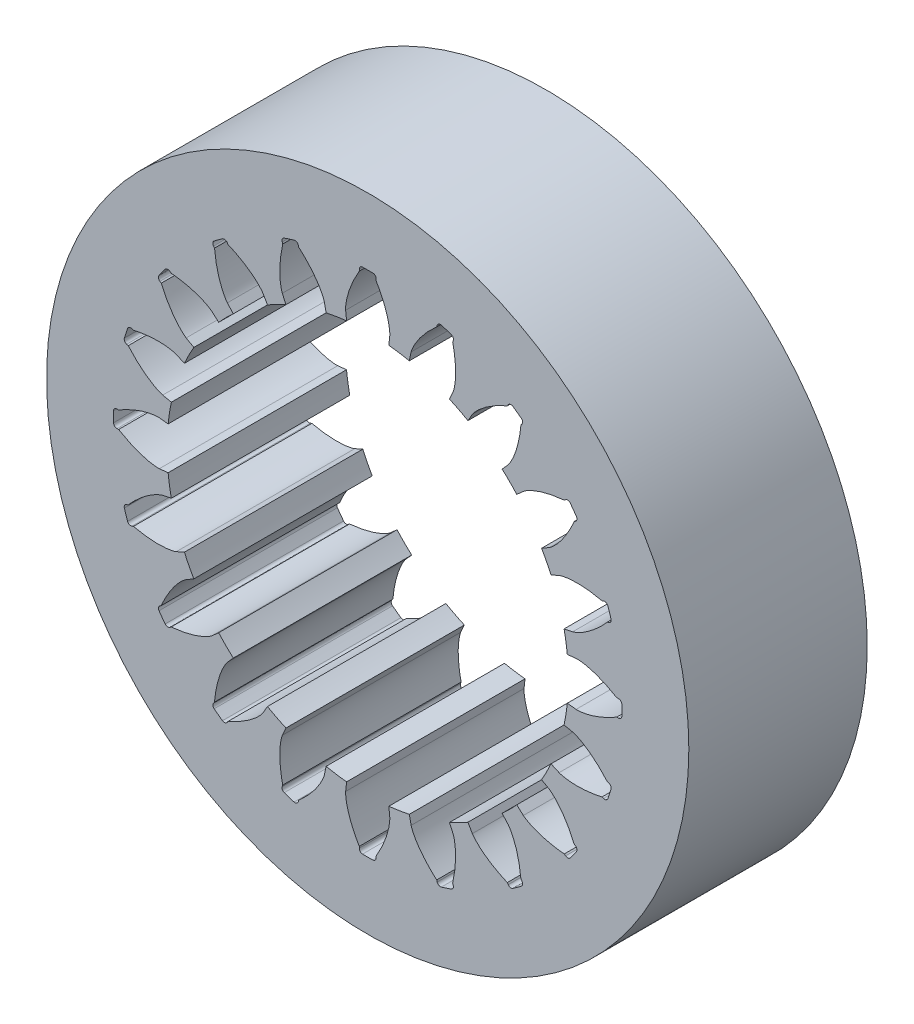
SolidWorks part; units mm, degrees
ref_plane "Front Plane" through (0, 0, 0) normal (0, 0, 1) x (1, 0, 0)
ref_plane "Top Plane" through (0, 0, 0) normal (0, 1, 0) x (1, 0, 0)
ref_plane "Right Plane" through (0, 0, 0) normal (1, 0, 0) x (0, 0, -1)
ref_axis "Gear Axis" through (0, 0, -0.5001) along (0, 0, 1)
sketch "Blank Sketch" plane through (0, 0, 0) normal (0, 0, 1) x (1, 0, 0)
  circle A0 centre (0, 0) radius 18
  circle A1 centre (0, 0) radius 11.25
  dimension "Rim" = 36
  dimension "Tip" = 22.5
extrude "Blank" add sketch "Blank Sketch" along normal blind 10
sketch "Tooth Space Sketch" plane through (0, 0, 0) normal (0, 0, 1) x (1, 0, 0)
  line L0 (11.6809, 1.2363) -> (9.9445, 1.0525)
  line L1 (11.6809, -1.2363) -> (9.9445, -1.0525)
  line L2 (9.9445, 1.0525) -> (9.9445, -1.0525)
  line L3 (13.9608, 0.4707) -> (14.0533, 0.4738)
  line L4 (13.9608, -0.4707) -> (14.0533, -0.4738)
  circle A0 centre (0, 0) radius 10 construction
  arc A1 (14.247, 0.2902) -> (14.0533, 0.4738) centre (14.0596, 0.2864) ccw
  arc A2 (14.0533, -0.4738) -> (14.247, -0.2902) centre (14.0596, -0.2864) ccw
  arc A3 (14.247, -0.2902) -> (14.247, 0.2902) centre (0, 0) ccw
  spline S0 degree 4 poles (11.6809, 1.2363) (11.6845, 1.2366) (11.6946, 1.2374) (11.7136, 1.2382) (11.7448, 1.2388) (11.7846, 1.2383) (11.8361, 1.2362) (11.8968, 1.2318) (11.9635, 1.2251) (12.0361, 1.2157) (12.1085, 1.2045) (12.1806, 1.1917) (12.2524, 1.1773) (12.3392, 1.1581) (12.4432, 1.1325) (12.5644, 1.0989) (12.7014, 1.0564) (12.8404, 1.0086) (12.9768, 0.9577) (13.114, 0.902) (13.2462, 0.845) (13.3827, 0.7815) (13.5084, 0.7205) (13.6482, 0.6474) (13.7608, 0.5871) (13.9081, 0.5023) (13.9948, 0.4507) (14.0959, 0.3886) (14.1405, 0.36) (14.168, 0.3425) knots 0 0 0 0 0 0.005377 0.015084 0.028532 0.04661 0.064855 0.092111 0.119476 0.146842 0.174209 0.201575 0.228941 0.256307 0.307035 0.361767 0.4165 0.471232 0.525964 0.580697 0.635429 0.690161 0.744894 0.799626 0.854358 0.909091 0.954545 1 1 1 1 1 construction
  spline S1 degree 4 poles (11.6809, 1.2363) (11.6845, 1.2366) (11.6946, 1.2374) (11.7136, 1.2382) (11.7448, 1.2388) (11.7846, 1.2383) (11.8361, 1.2362) (11.8968, 1.2318) (11.9635, 1.2251) (12.0361, 1.2157) (12.1085, 1.2045) (12.1806, 1.1917) (12.2524, 1.1773) (12.3392, 1.1581) (12.4432, 1.1325) (12.5644, 1.0989) (12.7014, 1.0564) (12.8404, 1.0086) (12.9768, 0.9577) (13.114, 0.902) (13.2462, 0.845) (13.3827, 0.7815) (13.5084, 0.7205) (13.6482, 0.6474) (13.7608, 0.5871) (13.8762, 0.5207) (13.9322, 0.4878) (13.9608, 0.4707) knots 0 0 0 0 0 0.005377 0.015084 0.028532 0.04661 0.064855 0.092111 0.119476 0.146842 0.174209 0.201575 0.228941 0.256307 0.307035 0.361767 0.4165 0.471232 0.525964 0.580697 0.635429 0.690161 0.744894 0.799626 0.854358 0.909091 0.909091 0.909091 0.909091 0.909091
  spline S2 degree 4 poles (11.6809, -1.2363) (11.6845, -1.2366) (11.6946, -1.2374) (11.7136, -1.2382) (11.7448, -1.2388) (11.7846, -1.2383) (11.8361, -1.2362) (11.8968, -1.2318) (11.9635, -1.2251) (12.0361, -1.2157) (12.1085, -1.2045) (12.1806, -1.1917) (12.2524, -1.1773) (12.3392, -1.1581) (12.4432, -1.1325) (12.5644, -1.0989) (12.7014, -1.0564) (12.8404, -1.0086) (12.9768, -0.9577) (13.114, -0.902) (13.2462, -0.845) (13.3827, -0.7815) (13.5084, -0.7205) (13.6482, -0.6474) (13.7608, -0.5871) (13.9081, -0.5023) (13.9948, -0.4507) (14.0959, -0.3886) (14.1405, -0.36) (14.168, -0.3425) knots 0 0 0 0 0 0.005377 0.015084 0.028532 0.04661 0.064855 0.092111 0.119476 0.146842 0.174209 0.201575 0.228941 0.256307 0.307035 0.361767 0.4165 0.471232 0.525964 0.580697 0.635429 0.690161 0.744894 0.799626 0.854358 0.909091 0.954545 1 1 1 1 1 construction
  spline S3 degree 4 poles (11.6809, -1.2363) (11.6845, -1.2366) (11.6946, -1.2374) (11.7136, -1.2382) (11.7448, -1.2388) (11.7846, -1.2383) (11.8361, -1.2362) (11.8968, -1.2318) (11.9635, -1.2251) (12.0361, -1.2157) (12.1085, -1.2045) (12.1806, -1.1917) (12.2524, -1.1773) (12.3392, -1.1581) (12.4432, -1.1325) (12.5644, -1.0989) (12.7014, -1.0564) (12.8404, -1.0086) (12.9768, -0.9577) (13.114, -0.902) (13.2462, -0.845) (13.3827, -0.7815) (13.5084, -0.7205) (13.6482, -0.6474) (13.7608, -0.5871) (13.8762, -0.5207) (13.9322, -0.4878) (13.9608, -0.4707) knots 0 0 0 0 0 0.005377 0.015084 0.028532 0.04661 0.064855 0.092111 0.119476 0.146842 0.174209 0.201575 0.228941 0.256307 0.307035 0.361767 0.4165 0.471232 0.525964 0.580697 0.635429 0.690161 0.744894 0.799626 0.854358 0.909091 0.909091 0.909091 0.909091 0.909091
  dimension "Root" = 14.25
  dimension "Fillet" = 0.1875
  dimension "Cap" = 20
extrude "Tooth Space" cut sketch "Tooth Space Sketch" against normal through all both and the other way through all both
pattern_circular "Teeth" count 20 over 360 about axis through (0, 0, -0.5001) along (0, 0, 1) of "Tooth Space"
equation "\"No. of Teeth\"= 20"
equation "\"Module\"= 1.25"
equation "\"Pressure Angle\"= 20"
equation "\"Inner Diameter\"= ( \"No. of Teeth\" - 2 ) * \"Module\""
equation "\"Pitch Diameter\"= \"No. of Teeth\" * \"Module\""
equation "\"Backlash\"= IIF ( \"Module\" <= 1 , 0.3 * \"Module\" , 0.3 )"
equation "\"Arc Length\"= ( ( \"Module\" * pi ) / 2 + \"Backlash\" )"
equation "\"Fillet Radius\"= 0.15 * \"Module\""
equation "\"Tooth Depth\"= IIF ( \"Module\" <= 1.25 , \"Module\" * 2.4 , \"Module\" * 2.25 )"
equation "\"Face Width\"= 10"
equation "\"Root Diameter\"= \"Inner Diameter\" + 2 * \"Tooth Depth\""
equation "\"Rim Diameter\"= \"Root Diameter\" + 6 * \"Module\""
equation "\"Base Diameter\"= \"Pitch Diameter\" * cos ( \"Pressure Angle\" )"
equation "\"Base Radius\"= \"Base Diameter\" / 2"
equation "\"Tooth Thickness\"= \"Module\" * pi - \"Arc Length\""
equation "\"Half Space Angle\"= ( \"Arc Length\" / \"Pitch Diameter\" ) * 180 / pi"
equation "\"Involute Fn\"= tan ( \"Pressure Angle\" ) - \"Pressure Angle\" * pi / 180"
equation "\"Flank Offset\"= 0 - \"Arc Length\" / \"Pitch Diameter\" - \"Involute Fn\""
equation "\"Tip Cap Diameter\"= \"Inner Diameter\" - 2 * \"Module\""
equation "\"Flank Start Diameter\"= IIF ( \"Base Diameter\" >= ( \"Inner Diameter\" - \"Module\" ) , \"Base Diameter\" , \"Inner Diameter\" - \"Module\" )"
equation "\"Flank End Diameter\"= \"Root Diameter\" - 3 * \"Fillet Radius\""
equation "\"Involute t1\"= ( abs ( ( \"Flank Start Diameter\" / \"Base Diameter\" ) ^ 2 - 1 ) ) ^ 0.5"
equation "\"Involute t2\"= ( abs ( ( \"Flank End Diameter\" / \"Base Diameter\" ) ^ 2 - 1 ) ) ^ 0.5"
equation "\"Flank Arc Radius\"= ( \"Pitch Diameter\" / 2 ) * sin ( \"Pressure Angle\" )"
equation "\"Flank Centre Angle\"= \"Half Space Angle\" - \"Pressure Angle\""
equation "\"Rim@Blank Sketch\"= \"Rim Diameter\""
equation "\"Tip@Blank Sketch\"= \"Inner Diameter\""
equation "\"Width@Blank\"= \"Face Width\""
equation "\"Root@Tooth Space Sketch\"= \"Root Diameter\" / 2"
equation "\"Fillet@Tooth Space Sketch\"= \"Fillet Radius\""
equation "\"Cap@Tooth Space Sketch\"= \"Tip Cap Diameter\""
equation "\"Count@Teeth\"= \"No. of Teeth\""
